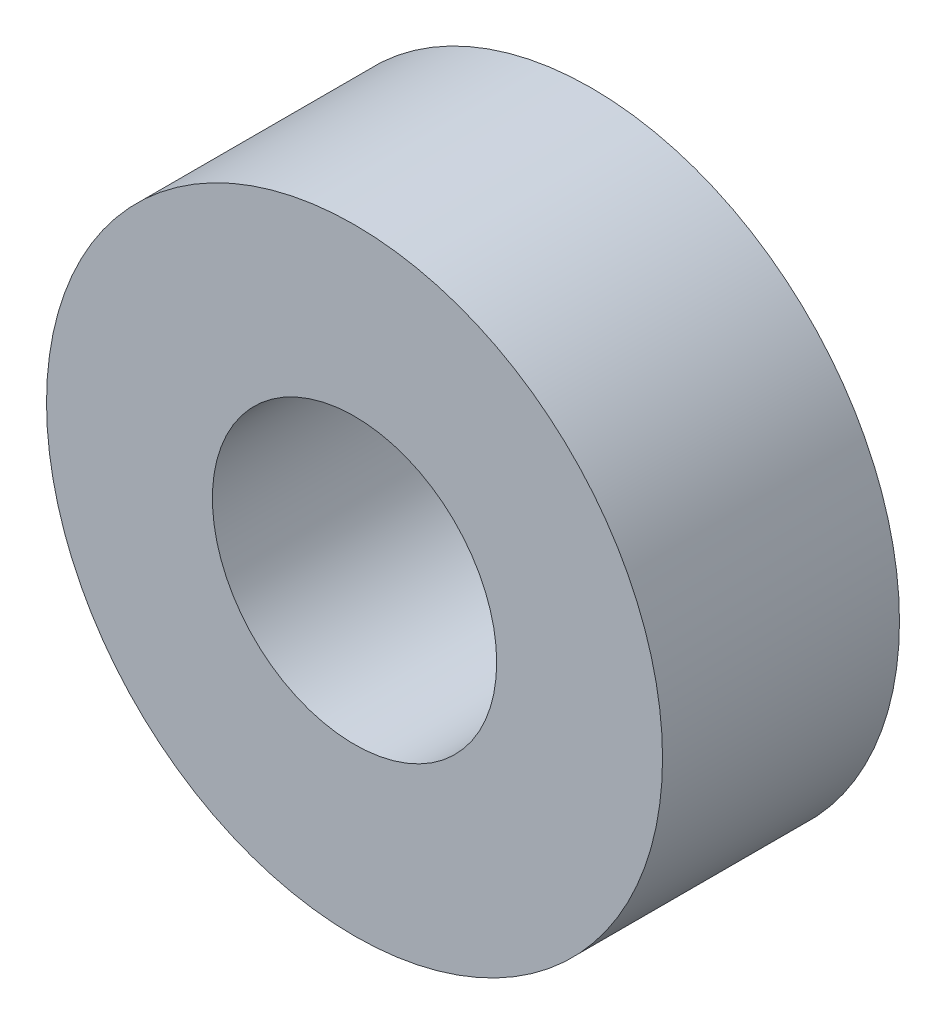
SolidWorks part; units mm, degrees
ref_plane "Front Plane" through (0, 0, 0) normal (0, 0, 1) x (1, 0, 0)
ref_plane "Top Plane" through (0, 0, 0) normal (0, 1, 0) x (1, 0, 0)
ref_plane "Right Plane" through (0, 0, 0) normal (1, 0, 0) x (0, 0, -1)
sketch "Sketch1" plane through (0, 0, 0) normal (0, 0, 1) x (1, 0, 0)
  circle A0 centre (-62, 0) radius 6.5
  circle A1 centre (-62, 0) radius 3
extrude "Boss-Extrude1" add sketch "Sketch1" against normal blind 5
